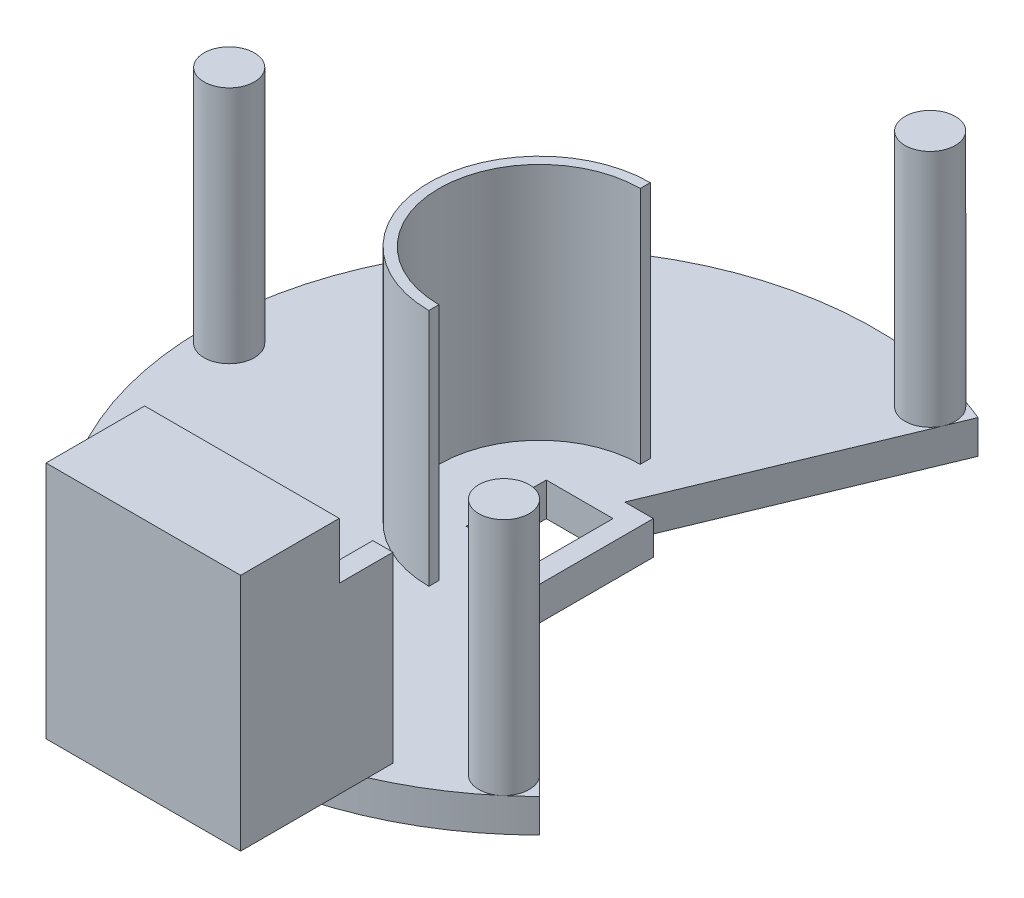
SolidWorks part; units mm, degrees
ref_plane "Front Plane" through (0, 0, 0) normal (0, 0, 1) x (1, 0, 0)
ref_plane "Top Plane" through (0, 0, 0) normal (0, 1, 0) x (1, 0, 0)
ref_plane "Right Plane" through (0, 0, 0) normal (1, 0, 0) x (0, 0, -1)
sketch "Sketch1" plane through (0, 0, 0) normal (0, 1, 0) x (1, 0, 0)
  line L0 (0, -50) -> (0, 0) construction
  line L1 (-4.975, 5.975) -> (4.975, 5.975)
  line L2 (-4.975, 5.975) -> (-4.975, -5.975)
  line L3 (-4.975, -5.975) -> (4.975, -5.975)
  line L4 (4.975, 5.975) -> (4.975, -5.975)
  line L5 (0, -5.975) -> (0, 5.975) construction
  line L6 (-4.975, 0) -> (4.975, 0) construction
  line L7 (7.975, -7.975) -> (35.3553, -35.3553)
  line L8 (0, 0) -> (0, 50) construction
  line L9 (3.7176, 8.975) -> (19.1342, 46.194)
  line L10 (3.7176, 8.975) -> (7.975, 8.975)
  line L11 (7.975, 8.975) -> (7.975, -7.975)
  line L12 (7.975, -7.975) -> (0, 0) construction
  line L13 (0, 0) -> (3.7176, 8.975) construction
  line L14 (5.891, -39.253) -> (10.3932, -48.9079)
  line L15 (-6.5, -42) -> (-6.5, -49.5757)
  arc A0 (10.3932, -48.9079) -> (-6.5, -49.5757) centre (0, 0) ccw
  arc A1 (5.891, -39.253) -> (-6.5, -42) centre (0, -42) ccw
  dimension "D1" = 100
  dimension "D5" = 13
  dimension "D2" = 11.95
  dimension "D3" = 9.95
  dimension "D4" = 45
  dimension "D6" = 42
  dimension "D7" = 22.5
  dimension "D8" = 3
  dimension "D9" = 3
  dimension "D10" = 38.7216
  dimension "D11" = 40.2855
  dimension "D12" = 25
extrude "Boss-Extrude2" add sketch "Sketch1" along normal blind 5 contours L9 A0 L7 L11 L10 A1 L1 L4 L3 L2
sketch "Sketch2" plane through (0, 5, 0) normal (0, 1, 0) x (1, 0, 0)
  line L0 (0, 0) -> (0, -50) construction
  line L1 (-5.85, -61.7) -> (17.15, -61.7)
  line L2 (-5.85, -61.7) -> (-5.85, -50)
  line L3 (-5.85, -50) -> (17.15, -50) construction
  line L4 (17.15, -61.7) -> (17.15, -50)
  line L5 (0, -55.85) -> (0, -50) construction
  line L6 (17.15, -50) -> (17.15, -42)
  line L7 (-8.85, -64.7) -> (20.15, -64.7)
  line L8 (-8.85, -64.7) -> (-8.85, -42)
  line L9 (-5.85, -50) -> (17.15, -50)
  line L10 (20.15, -64.7) -> (20.15, -50)
  line L11 (20.15, -50) -> (20.15, -42)
  line L12 (-6.5, -49.5757) -> (-6.5, -42)
  line L13 (-5.85, -50) -> (-6.5, -49.5757)
  line L14 (-6.5, -42) -> (-6.5, -49.5757) construction
  line L15 (-8.85, -42) -> (-6.5, -42)
  line L16 (17.15, -42) -> (20.15, -42)
  circle A1 centre (0, -55.85) radius 5.85 construction
  arc M8 (19.1342, 46.194) -> (-6.5, -49.5757) centre (0, 0) ccw
  arc M13 (10.3932, -48.9079) -> (35.3553, -35.3553) centre (0, 0) ccw
  line M14 (-6.5, -49.5757) -> (-6.5, -42)
  dimension "D2" = 23
  dimension "D3" = 11.7
  dimension "D4" = 3
  dimension "D5" = 3
  dimension "D6" = 3
extrude "Boss-Extrude4" add sketch "Sketch2" along normal offset from surface (27.23 mm away) 32.23 contours L2 L13 L8 L7 L10 L11 L6 L4 L1 M8 M13 | L15 L8 M8 M14 | L16 L6 L11 M13 up to face at (2.5227, 0, 15.6824)
sketch "Sketch3" plane through (0, 32.23, 0) normal (0, 1, 0) x (1, 0, 0)
  line L0 (20.15, -64.7) -> (20.15, -42) construction
  line L1 (-8.85, -64.7) -> (20.15, -64.7)
  line L2 (-8.85, -64.7) -> (-8.85, -50)
  line L3 (-8.85, -50) -> (20.15, -50)
  line L4 (20.15, -64.7) -> (20.15, -50)
extrude "Boss-Extrude5" add sketch "Sketch3" along normal blind 3
sketch "Sketch4" plane through (0, 5, 0) normal (0, 1, 0) x (1, 0, 0)
  line L0 (0, 16.5) -> (0, 15)
  line L1 (0, -15) -> (0, -16.5)
  arc A0 (0, 15) -> (0, -15) centre (0, 0) ccw
  arc A1 (0, 16.5) -> (0, -16.5) centre (0, 0) ccw
  dimension "D1" = 30
  dimension "D2" = 33
extrude "Boss-Extrude6" add sketch "Sketch4" along normal offset from surface (35.6 mm away) 40.6 up to face at (2.5227, 0, 15.6824)
sketch "Sketch7" plane through (0, 35.23, 0) normal (0, 1, 0) x (1, 0, 0)
  line L4 (-8.85, -50) -> (-8.85, -64.7)
  line L5 (-8.85, -64.7) -> (20.15, -64.7)
  line L6 (20.15, -64.7) -> (20.15, -50)
  line L7 (20.15, -50) -> (-8.85, -50)
  line L8 (-8.85, -50) -> (-8.85, -64.7)
  line L9 (-8.85, -64.7) -> (20.15, -64.7)
  line L10 (20.15, -64.7) -> (20.15, -50)
  line L11 (20.15, -50) -> (-8.85, -50)
  dimension "D1" = 0
extrude "Boss-Extrude7" add sketch "Sketch7" along normal up to surface (5.37 mm away) up to face at (-7.875, 40.6, 0)
sketch "Sketch8" plane through (0, 5, 0) normal (0, 1, 0) x (1, 0, 0)
  line L0 (7.975, -7.975) -> (35.3553, -35.3553) construction
  line L1 (3.7176, 8.975) -> (19.1342, 46.194) construction
  circle A0 centre (14.1763, 44.0238) radius 3.75
  circle A1 centre (29.9444, -35.2477) radius 3.75
  circle A2 centre (-46.25, 0) radius 3.75
  arc A3 (19.1342, 46.194) -> (-8.85, -49.2105) centre (0, 0) ccw construction
  arc A4 (20.15, -45.76) -> (35.3553, -35.3553) centre (0, 0) ccw construction
  point P16 (-45.5261, 8.1509)
  dimension "D1" = 7.5
  dimension "D2" = 7.5
  dimension "D3" = 7.5
extrude "Boss-Extrude8" add sketch "Sketch8" along normal up to surface (35.6 mm away) up to face at (-7.875, 40.6, 0)
